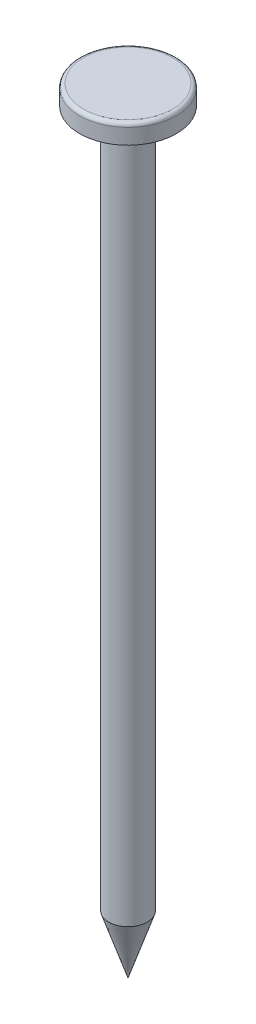
SolidWorks part; units mm, degrees
material "AISI 1015 Aço, trefilado (SS)"
ref_plane "Plano frontal" through (0, 0, 0) normal (0, 0, 1) x (1, 0, 0)
ref_plane "Plano superior" through (0, 0, 0) normal (0, 1, 0) x (1, 0, 0)
ref_plane "Plano direito" through (0, 0, 0) normal (1, 0, 0) x (0, 0, -1)
sketch "Esboço2" plane through (0, 0, 0) normal (0, 0, 1) x (1, 0, 0)
  line L0 (0, -4.4661) -> (0, 27.4235) construction
  line L1 (0, 0) -> (0, 20)
  line L2 (0, 20) -> (1.25, 20)
  line L3 (1.25, 20) -> (1.25, 19.5)
  line L4 (1.25, 19.5) -> (0.5, 19.5)
  line L5 (0.5, 19.5) -> (0.5, 1.5)
  line L6 (0.5, 1.5) -> (0, 0)
  dimension "D1" = 2.5
  dimension "D2" = 1
  dimension "D3" = 0.5
  dimension "D4" = 1.5
  dimension "D5" = 20
revolve "Revolução5" add sketch "Esboço2" angle 360 about L0
fillet "Filete1" radius 0.1 1 edges at (0, 20, -1.25)
